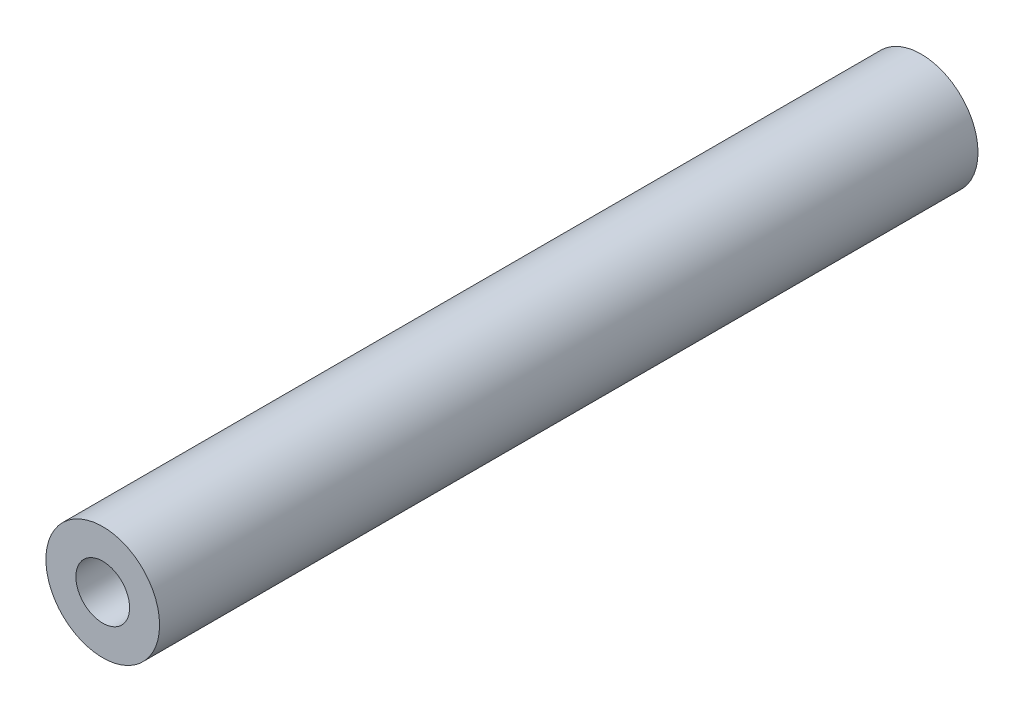
SolidWorks part; units mm, degrees
ref_plane "Front Plane" through (0, 0, 0) normal (0, 0, 1) x (1, 0, 0)
ref_plane "Top Plane" through (0, 0, 0) normal (0, 1, 0) x (1, 0, 0)
ref_plane "Right Plane" through (0, 0, 0) normal (1, 0, 0) x (0, 0, -1)
sketch "Sketch1" plane through (0, 0, 0) normal (0, 0, 1) x (1, 0, 0)
  circle A0 centre (0, 0) radius 3.175
  circle A1 centre (0, 0) radius 1.5
  dimension "D1" = 6.35
  dimension "D2" = 3
extrude "Boss-Extrude1" add sketch "Sketch1" along normal blind 45.72
